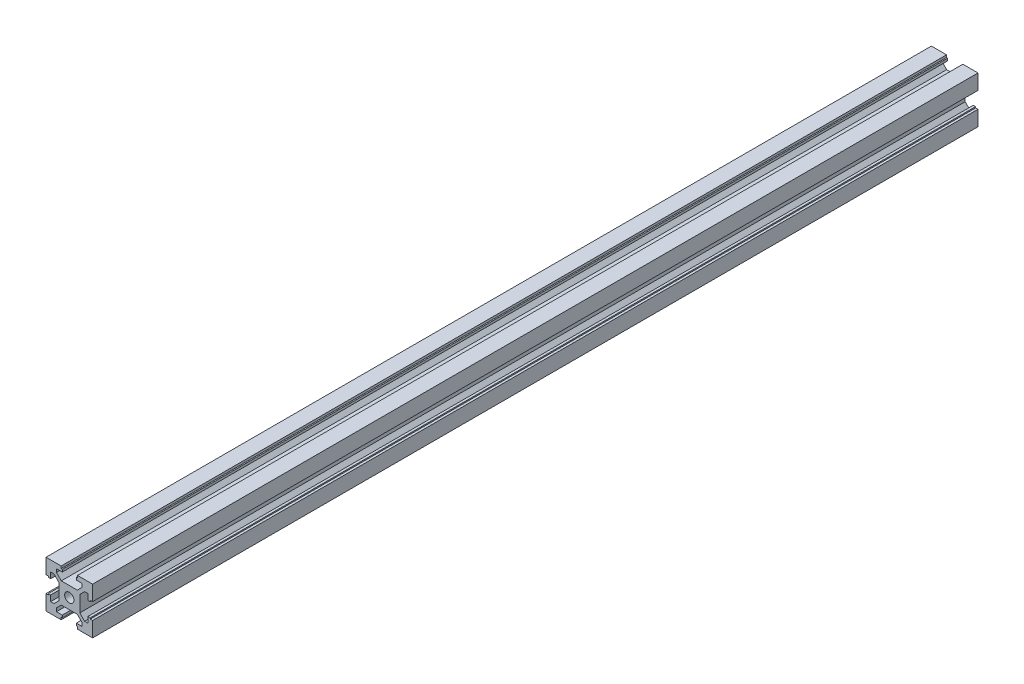
SolidWorks part; units mm, degrees
ref_plane "Front Plane" through (0, 0, 0) normal (0, 0, 1) x (1, 0, 0)
ref_plane "Top Plane" through (0, 0, 0) normal (0, 1, 0) x (1, 0, 0)
ref_plane "Right Plane" through (0, 0, 0) normal (1, 0, 0) x (0, 0, -1)
sketch "Sketch1" plane through (0, 0, 0) normal (0, 0, 1) x (1, 0, 0)
  line L0 (0, 10) -> (0, -4.5007) construction
  line L1 (-10, -10) -> (-3.5, -10)
  line L2 (-10, -10) -> (-10, -3.5)
  line L3 (-10, 10) -> (-3.5, 10)
  line L4 (10, -10) -> (10, -3.5)
  line L5 (-10, -10) -> (10, 10) construction
  line L6 (-10, 10) -> (10, -10) construction
  line L7 (-10, 0) -> (10, 0) construction
  line L8 (-3.5, 10) -> (-3.5, 9)
  line L9 (-3.44, -4.5007) -> (3.44, -4.5007)
  line L10 (-4.5007, -3.44) -> (-4.5007, 3.44)
  line L11 (-3.44, 4.5007) -> (3.44, 4.5007)
  line L12 (4.5007, -3.44) -> (4.5007, 3.44)
  line L13 (-10, -10) -> (10, 10) construction
  line L14 (-10, 10) -> (10, -10) construction
  line L15 (-3.5, 9) -> (-3, 9)
  line L16 (-3, 9) -> (-3, 8)
  line L17 (-3, 8) -> (-5.5, 8)
  line L18 (-5.5, 8) -> (-5.5, 6.5607)
  line L19 (-5.5, 6.5607) -> (-3.44, 4.5007)
  line L20 (3.5, 10) -> (10, 10)
  line L21 (3.5, 9) -> (3, 9)
  line L22 (5.5, 6.5607) -> (3.44, 4.5007)
  line L23 (5.5, 8) -> (5.5, 6.5607)
  line L24 (3, 8) -> (5.5, 8)
  line L25 (3, 9) -> (3, 8)
  line L26 (3.5, 10) -> (3.5, 9)
  line L27 (-3.5, 10) -> (3.5, 10) construction
  line L28 (5.5, -6.5607) -> (3.44, -4.5007)
  line L29 (5.5, -8) -> (5.5, -6.5607)
  line L30 (3, -8) -> (5.5, -8)
  line L31 (3, -9) -> (3, -8)
  line L32 (3.5, -9) -> (3, -9)
  line L33 (3.5, -10) -> (3.5, -9)
  line L34 (-3.5, -9) -> (-3, -9)
  line L35 (-5.5, -6.5607) -> (-3.44, -4.5007)
  line L36 (-5.5, -8) -> (-5.5, -6.5607)
  line L37 (-3, -8) -> (-5.5, -8)
  line L38 (-3, -9) -> (-3, -8)
  line L39 (-3.5, -10) -> (-3.5, -9)
  line L40 (-6.5607, -5.5) -> (-4.5007, -3.44)
  line L41 (-8, -5.5) -> (-6.5607, -5.5)
  line L42 (-8, -3) -> (-8, -5.5)
  line L43 (-10, -3.5) -> (-9, -3.5)
  line L44 (-9, -3) -> (-8, -3)
  line L45 (-9, -3.5) -> (-9, -3)
  line L46 (6.5607, -5.5) -> (4.5007, -3.44)
  line L47 (8, -5.5) -> (6.5607, -5.5)
  line L48 (8, -3) -> (8, -5.5)
  line L49 (9, -3) -> (8, -3)
  line L50 (9, -3.5) -> (9, -3)
  line L51 (10, -3.5) -> (9, -3.5)
  line L52 (-6.5607, 5.5) -> (-4.5007, 3.44)
  line L53 (-8, 5.5) -> (-6.5607, 5.5)
  line L54 (-8, 3) -> (-8, 5.5)
  line L55 (-9, 3) -> (-8, 3)
  line L56 (-9, 3.5) -> (-9, 3)
  line L57 (-10, 3.5) -> (-9, 3.5)
  line L58 (10, 3.5) -> (9, 3.5)
  line L59 (9, 3.5) -> (9, 3)
  line L60 (9, 3) -> (8, 3)
  line L61 (8, 3) -> (8, 5.5)
  line L62 (8, 5.5) -> (6.5607, 5.5)
  line L63 (6.5607, 5.5) -> (4.5007, 3.44)
  line L64 (10, 3.5) -> (10, 10)
  line L65 (-10, 3.5) -> (-10, 10)
  line L66 (-10, 3.5) -> (-10, -3.5) construction
  line L67 (10, 3.5) -> (10, -3.5) construction
  line L68 (3.5, -10) -> (10, -10)
  line L69 (-3.5, -10) -> (3.5, -10) construction
  circle A0 centre (0, 0) radius 2
  point P0 (0, 0)
  point P10 (0, 0)
  dimension "D10" = 4
  dimension "D1" = 20
  dimension "D2" = 14.5007
  dimension "D3" = 0.75
  dimension "D4" = 3.5
  dimension "D5" = 3
  dimension "D6" = 1
  dimension "D7" = 1
  dimension "D8" = 3.44
  dimension "D9" = 5.5
extrude "Boss-Extrude1" add sketch "Sketch1" along normal blind 380
